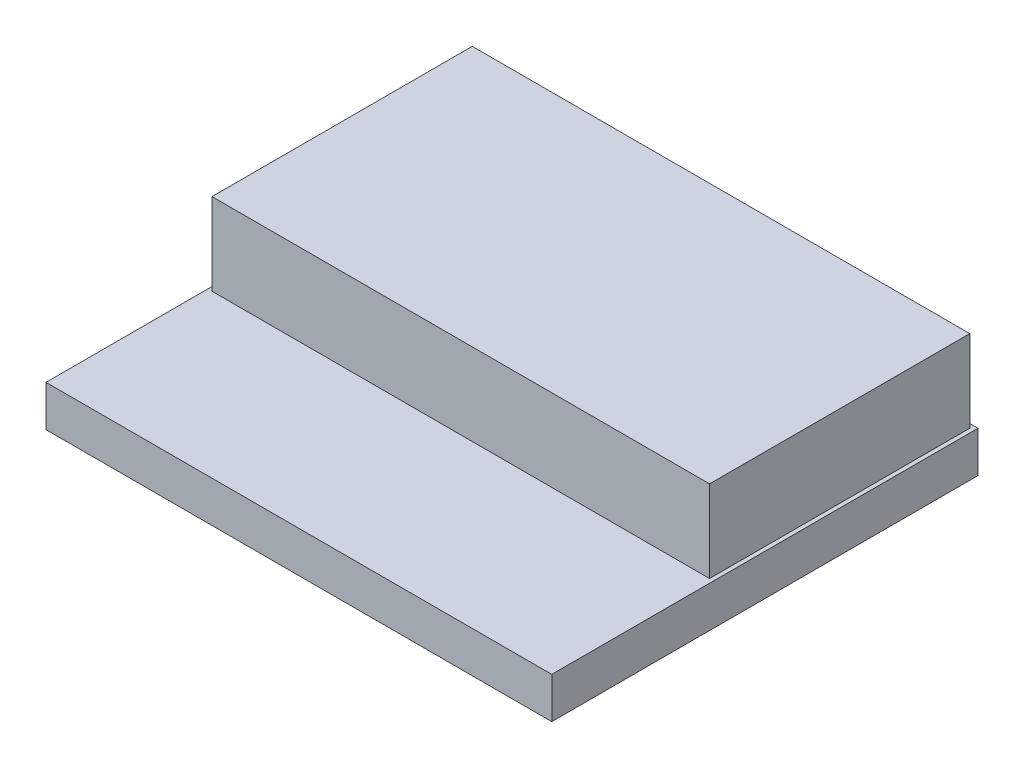
SolidWorks part; units mm, degrees
ref_plane "Front Plane" through (0, 0, 0) normal (0, 0, 1) x (1, 0, 0)
ref_plane "Top Plane" through (0, 0, 0) normal (0, 1, 0) x (1, 0, 0)
ref_plane "Right Plane" through (0, 0, 0) normal (1, 0, 0) x (0, 0, -1)
sketch "Sketch1" plane through (0, 0, 0) normal (0, 1, 0) x (1, 0, 0)
  line L1 (-6.17, -5.2) -> (6.17, -5.2)
  line L2 (-6.17, -5.2) -> (-6.17, 5.2)
  line L3 (-6.17, 5.2) -> (6.17, 5.2)
  line L4 (6.17, -5.2) -> (6.17, 5.2)
  line L5 (-6.17, -5.2) -> (6.17, 5.2) construction
  line L6 (-6.17, 5.2) -> (6.17, -5.2) construction
  point P0 (0, 0)
  dimension "D1" = 12.34
  dimension "D2" = 10.4
extrude "Boss-Extrude1" add sketch "Sketch1" along normal blind 1
sketch "Sketch2" plane through (0, 1, 0) normal (0, 1, 0) x (1, 0, 0)
  line L4 (-6.07, -1.25) -> (6.07, -1.25)
  line L8 (6.07, -5.1) -> (6.07, 5.1)
  line L9 (6.07, 5.1) -> (-6.07, 5.1)
  line L10 (-6.07, 5.1) -> (-6.07, -5.1)
  line L11 (-6.07, -5.1) -> (6.07, -5.1)
  line L12 (6.07, -1.25) -> (6.07, 5.1)
  line L13 (6.07, 5.1) -> (-6.07, 5.1)
  line L14 (-6.07, 5.1) -> (-6.07, -1.25)
  dimension "D2" = 6.35
  dimension "D1" = 0.1
extrude "Boss-Extrude2" add sketch "Sketch2" along normal offset from surface (2 mm away) 3 up to face at (0, 0, 0)
sketch "Sketch3" plane through (0, 0, 0) normal (0, -1, 0) x (1, 0, 0)
  line L8 (2.3, -1.33) -> (2.3, 1.33)
  line L9 (2.3, 1.33) -> (-2.3, 1.33)
  line L10 (-2.3, 1.33) -> (-2.3, -1.33)
  line L11 (-2.3, -1.33) -> (2.3, -1.33)
  line L12 (2.3, -1.33) -> (2.3, 1.33)
  line L13 (2.3, 1.33) -> (-2.3, 1.33)
  line L14 (-2.3, 1.33) -> (-2.3, -1.33)
  line L15 (-2.3, -1.33) -> (2.3, -1.33)
  dimension "D1" = 3.87
extrude "Boss-Extrude3" add sketch "Sketch3" along normal blind 1
